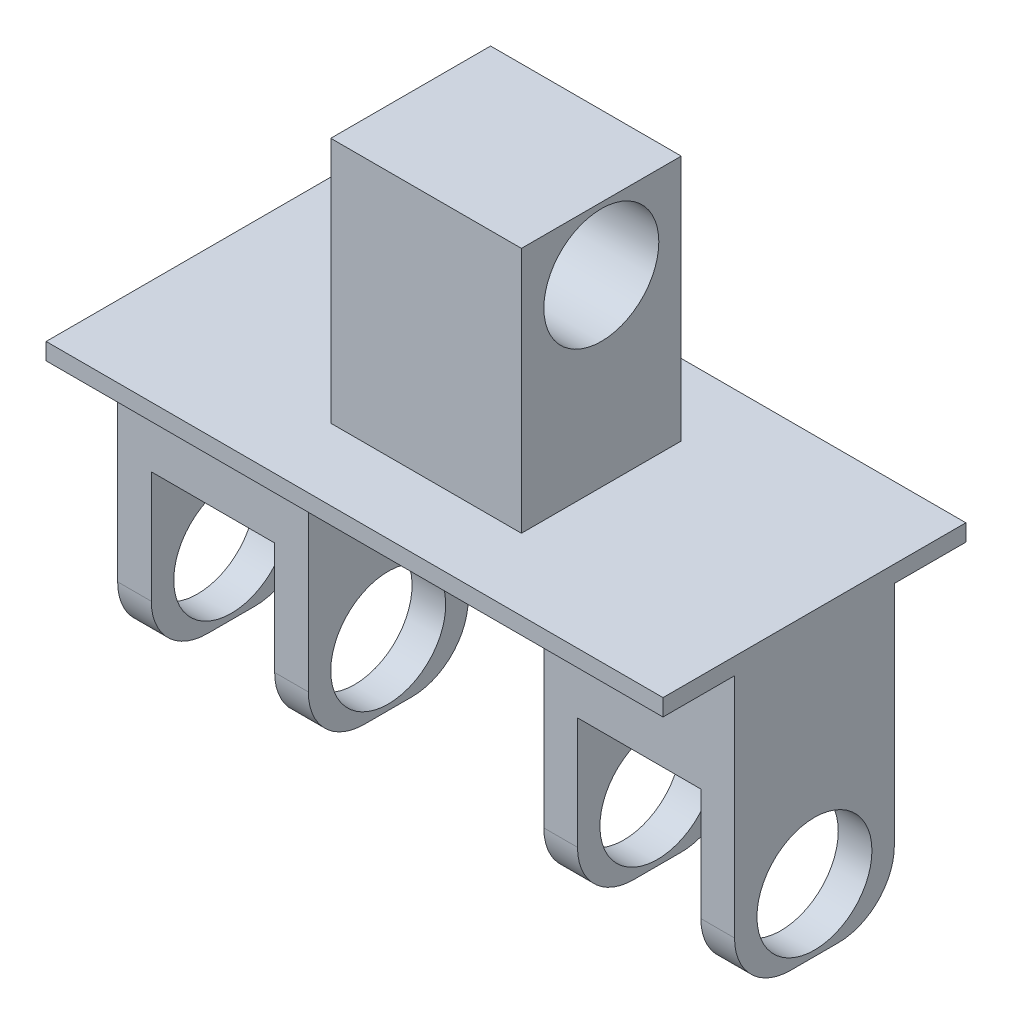
SolidWorks part; units mm, degrees
ref_plane "Front Plane" through (0, 0, 0) normal (0, 0, 1) x (1, 0, 0)
ref_plane "Top Plane" through (0, 0, 0) normal (0, 1, 0) x (1, 0, 0)
ref_plane "Right Plane" through (0, 0, 0) normal (1, 0, 0) x (0, 0, -1)
sketch "Sketch1" plane through (0, 0, 0) normal (0, 1, 0) x (1, 0, 0)
  line L1 (-55, 27) -> (55, 27)
  line L2 (-55, 27) -> (-55, -27)
  line L3 (-55, -27) -> (55, -27)
  line L4 (55, 27) -> (55, -27)
  line L5 (-55, 27) -> (55, -27) construction
  line L6 (-55, -27) -> (55, 27) construction
  point P0 (0, 0)
  dimension "D1" = 110
  dimension "D2" = 54
extrude "Boss-Extrude1" add sketch "Sketch1" along normal blind 3
sketch "Sketch2" plane through (0, 0, 0) normal (0, -1, 0) x (1, 0, 0)
  line L0 (0, 0) -> (0, -25.0818) construction
  line L1 (55, 27) -> (55, -27) construction
  line L2 (55, 14.25) -> (21, 14.25)
  line L3 (55, 14.25) -> (55, -14.25)
  line L4 (55, -14.25) -> (21, -14.25)
  line L5 (21, 14.25) -> (21, -14.25)
  line L7 (55, -27) -> (-55, -27) construction
  line L10 (-21, 14.25) -> (-21, -14.25)
  line L11 (-55, -14.25) -> (-21, -14.25)
  line L12 (-55, 14.25) -> (-55, -14.25)
  line L13 (-55, 14.25) -> (-21, 14.25)
  dimension "D1" = 34
  dimension "D2" = 28.5
  dimension "D3" = 12.75
extrude "Boss-Extrude2" add sketch "Sketch2" along normal blind 50.5
sketch "Sketch3" plane through (55, 0, 0) normal (1, 0, 0) x (0, 0, -1)
  line L0 (14.25, -50.5) -> (-14.25, -50.5) construction
  circle A0 centre (0, -39.25) radius 10.25
  dimension "D1" = 11.25
extrude "Cut-Extrude1" cut sketch "Sketch3" against normal through all both and the other way through all
sketch "Sketch4" plane through (0, 0, 14.25) normal (0, 0, 1) x (1, 0, 0)
  line L0 (0, 0) -> (0, -16.0317) construction
  line L1 (55, -50.5) -> (49, -50.5)
  line L2 (55, -50.5) -> (55, -20.5)
  line L3 (55, -20.5) -> (49, -20.5)
  line L4 (49, -50.5) -> (49, -20.5)
  line L5 (21, -50.5) -> (27, -50.5)
  line L6 (21, -50.5) -> (21, -20.5)
  line L7 (21, -20.5) -> (27, -20.5)
  line L8 (27, -50.5) -> (27, -20.5)
  line L9 (27, -20.5) -> (49, -20.5)
  line L10 (27, -20.5) -> (27, -50.5)
  line L11 (27, -50.5) -> (49, -50.5)
  line L12 (49, -20.5) -> (49, -50.5)
  line L13 (-55, 0) -> (55, 0) construction
  line L14 (-49, -20.5) -> (-49, -50.5)
  line L15 (-27, -50.5) -> (-49, -50.5)
  line L16 (-27, -20.5) -> (-27, -50.5)
  line L17 (-27, -20.5) -> (-49, -20.5)
  line L18 (-27, -50.5) -> (-27, -20.5)
  line L19 (-21, -20.5) -> (-27, -20.5)
  line L20 (-21, -50.5) -> (-21, -20.5)
  line L21 (-21, -50.5) -> (-27, -50.5)
  line L22 (-49, -50.5) -> (-49, -20.5)
  line L23 (-55, -20.5) -> (-49, -20.5)
  line L24 (-55, -50.5) -> (-55, -20.5)
  line L25 (-55, -50.5) -> (-49, -50.5)
  line M8 (21, -50.5) -> (55, -50.5)
  dimension "D1" = 30
  dimension "D2" = 6
  dimension "D3" = 6
extrude "Cut-Extrude2" cut sketch "Sketch4" against normal through all both and the other way through all contours L9 L8 L4 M8 | L16 L17 L14 L15
fillet "Fillet1" radius 10 8 edges at (-24, -50.5, 14.25) (-52, -50.5, 14.25) (-24, -50.5, -14.25) (-52, -50.5, -14.25) (24, -50.5, -14.25) (52, -50.5, -14.25) (24, -50.5, 14.25) (52, -50.5, 14.25)
sketch "Sketch5" plane through (0, 3, 0) normal (0, 1, 0) x (1, 0, 0)
  line L1 (-17, 14.25) -> (17, 14.25)
  line L2 (-17, 14.25) -> (-17, -14.25)
  line L3 (-17, -14.25) -> (17, -14.25)
  line L4 (17, 14.25) -> (17, -14.25)
  line L5 (-17, 14.25) -> (17, -14.25) construction
  line L6 (-17, -14.25) -> (17, 14.25) construction
  point P0 (0, 0)
  dimension "D1" = 34
  dimension "D2" = 28.5
extrude "Boss-Extrude3" add sketch "Sketch5" along normal blind 44
sketch "Sketch6" plane through (17, 0, 0) normal (1, 0, 0) x (0, 0, -1)
  line L0 (-14.25, 47) -> (14.25, 47) construction
  circle A0 centre (0, 35.75) radius 10.25
  dimension "D1" = 20.5
  dimension "D2" = 11.25
extrude "Cut-Extrude3" cut sketch "Sketch6" against normal through all both and the other way through all
